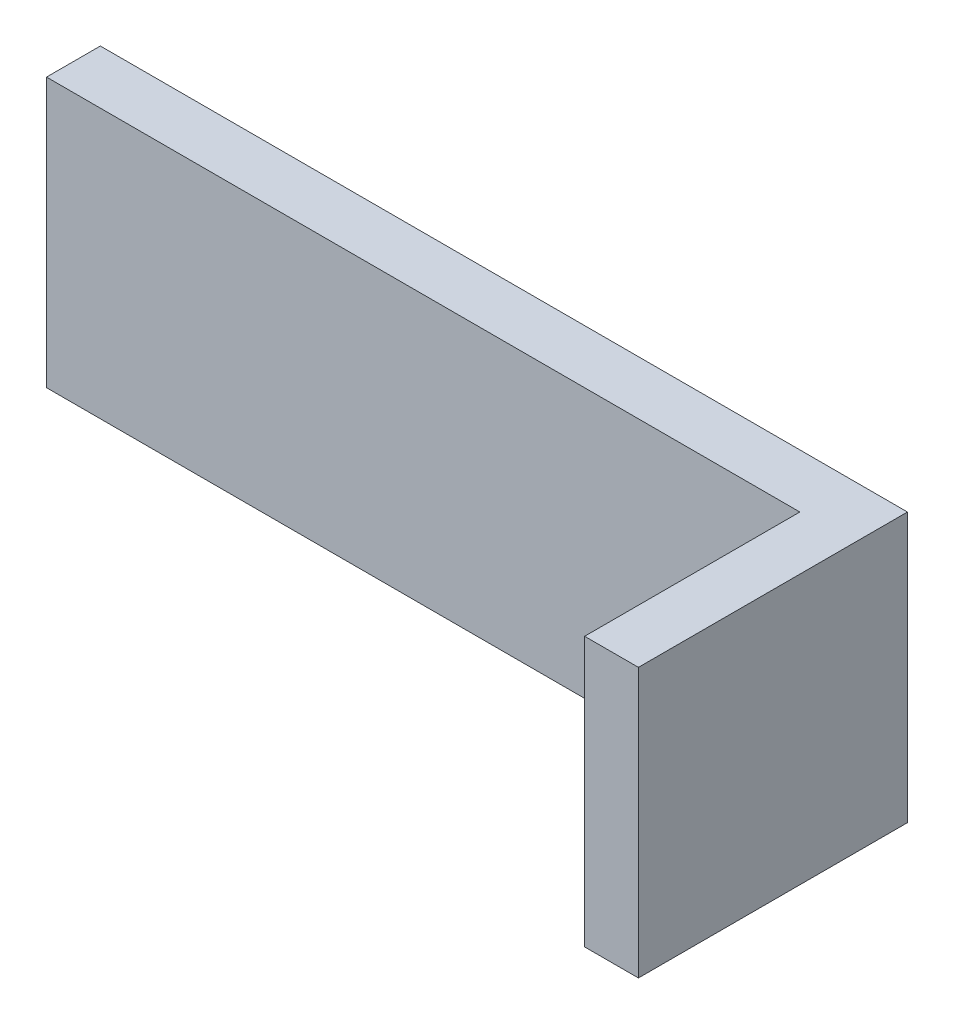
SolidWorks part; units mm, degrees
ref_plane "Front" through (0, 0, 0) normal (0, 0, 1) x (1, 0, 0)
ref_plane "Top" through (0, 0, 0) normal (0, 1, 0) x (1, 0, 0)
ref_plane "Right" through (0, 0, 0) normal (1, 0, 0) x (0, 0, -1)
sketch "Sketch1" plane through (0, 0, 0) normal (0, 0, 1) x (1, 0, 0)
  line L1 (75, -25) -> (-75, -25)
  line L2 (75, -25) -> (75, 25)
  line L3 (75, 25) -> (-75, 25)
  line L4 (-75, -25) -> (-75, 25)
  line L5 (75, -25) -> (-75, 25) construction
  line L6 (75, 25) -> (-75, -25) construction
  point P0 (0, 0)
  dimension "D1" = 50
  dimension "D2" = 150
extrude "Boss-Extrude1" add sketch "Sketch1" along normal blind 50
sketch "Sketch2" plane through (0, -25, 0) normal (0, -1, 0) x (1, 0, 0)
  line L1 (-75, 50) -> (65, 50)
  line L2 (-75, 50) -> (-75, 10)
  line L3 (-75, 10) -> (65, 10)
  line L4 (65, 50) -> (65, 10)
  dimension "D1" = 140
  dimension "D2" = 40
extrude "Cut-Extrude1" cut sketch "Sketch2" against normal blind 50
